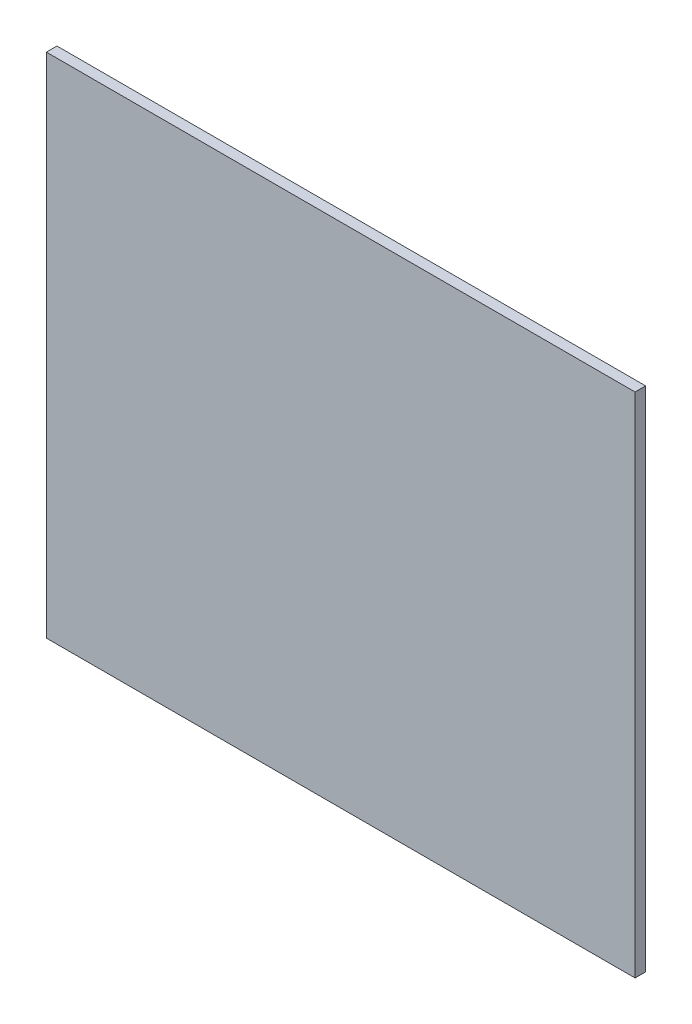
SolidWorks part; units mm, degrees
ref_plane "Front Plane" through (0, 0, 0) normal (0, 0, 1) x (1, 0, 0)
ref_plane "Top Plane" through (0, 0, 0) normal (0, 1, 0) x (1, 0, 0)
ref_plane "Right Plane" through (0, 0, 0) normal (1, 0, 0) x (0, 0, -1)
sketch "Sketch1" plane through (0, 0, 0) normal (0, 0, 1) x (1, 0, 0)
  line L1 (0, 0) -> (176.784, 0)
  line L2 (0, 0) -> (0, 152.4)
  line L3 (0, 152.4) -> (176.784, 152.4)
  line L4 (176.784, 0) -> (176.784, 152.4)
  dimension "D1" = 176.784
  dimension "D2" = 152.4
extrude "Boss-Extrude1" add sketch "Sketch1" along normal blind 3.175
